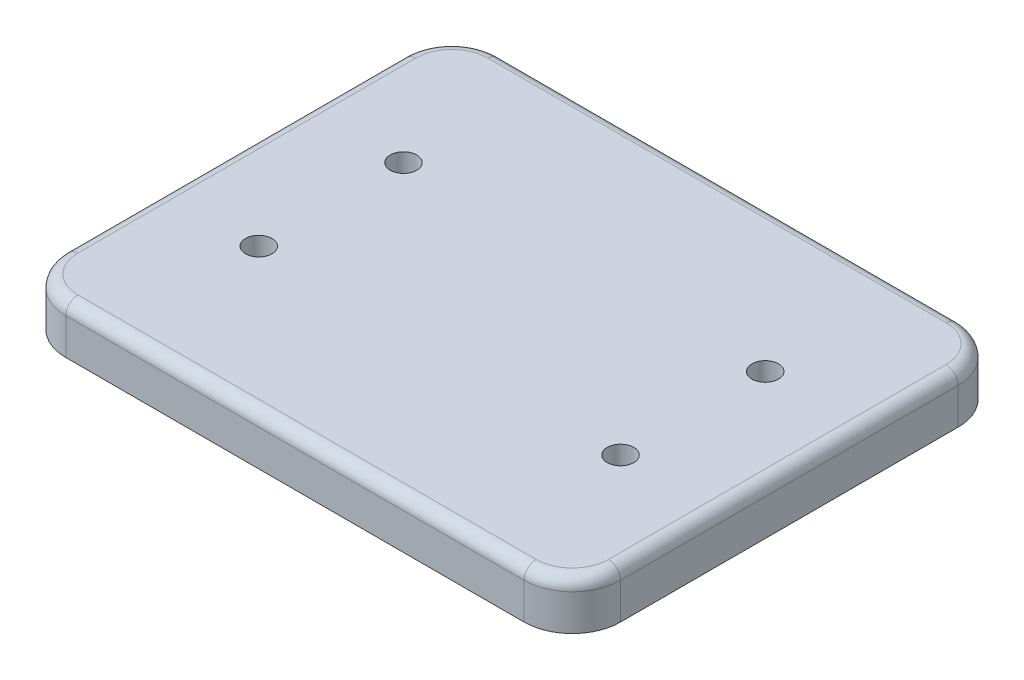
SolidWorks part; units mm, degrees
ref_plane "Front Plane" through (0, 0, 0) normal (0, 0, 1) x (1, 0, 0)
ref_plane "Top Plane" through (0, 0, 0) normal (0, 1, 0) x (1, 0, 0)
ref_plane "Right Plane" through (0, 0, 0) normal (1, 0, 0) x (0, 0, -1)
sketch "Sketch1" plane through (0, 0, 0) normal (0, 1, 0) x (1, 0, 0)
  line L1 (-95, -90) -> (95, -90)
  line L2 (-115, -70) -> (-115, 70)
  line L3 (-95, 90) -> (95, 90)
  line L4 (115, -70) -> (115, 70)
  line L5 (-115, -90) -> (115, 90) construction
  line L6 (-115, 90) -> (115, -90) construction
  arc A0 (-95, 90) -> (-115, 70) centre (-95, 70) ccw
  arc A1 (-95, -90) -> (-115, -70) centre (-95, -70) cw
  arc A2 (115, -70) -> (95, -90) centre (95, -70) cw
  arc A3 (115, 70) -> (95, 90) centre (95, 70) ccw
  point P0 (0, 0)
  dimension "D3" = 20
  dimension "D4" = 20
  dimension "D1" = 230
  dimension "D2" = 180
extrude "Boss-Extrude1" add sketch "Sketch1" against normal blind 20
fillet "Fillet1" radius 5 8 edges at (0, 0, -90) (109.1421, 0, -84.1421) (115, 0, 0) (109.1421, 0, 84.1421) (0, 0, 90) (-109.1421, 0, 84.1421) (-115, 0, 0) (-109.1421, 0, -84.1421)
sketch "Sketch3" plane through (0, 0, 0) normal (0, 1, 0) x (1, 0, 0)
  circle A0 centre (-75, 30) radius 5.5
  point P3 (0, 0)
  dimension "D2" = 11
  dimension "D3" = 75
  dimension "D4" = 30
extrude "Cut-Extrude1" cut sketch "Sketch3" against normal through all
sketch "Sketch4" plane through (0, -20, 0) normal (0, -1, 0) x (1, 0, 0)
  circle A0 centre (-75, -30) radius 9
extrude "Cut-Extrude2" cut sketch "Sketch4" against normal blind 11
mirror "Mirror1" about plane through (0, 0, 0) normal (1, 0, 0) of "Cut-Extrude2", "Cut-Extrude1"
mirror "Mirror2" about plane through (0, 0, 0) normal (0, 0, 1) of "Mirror1", "Cut-Extrude1", "Cut-Extrude2"
